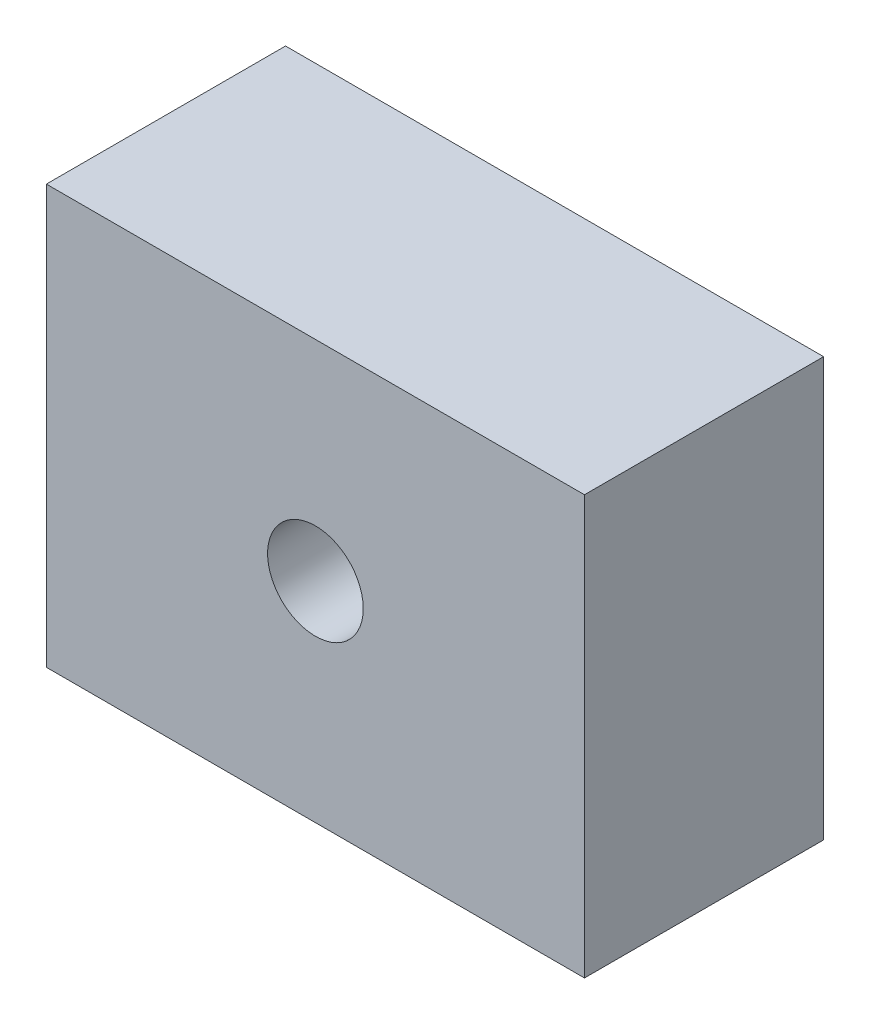
SolidWorks part; units mm, degrees
ref_plane "Front" through (0, 0, 0) normal (0, 0, 1) x (1, 0, 0)
ref_plane "Top" through (0, 0, 0) normal (0, 1, 0) x (1, 0, 0)
ref_plane "Right" through (0, 0, 0) normal (1, 0, 0) x (0, 0, -1)
sketch "Sketch1" plane through (0, 0, 0) normal (0, 0, 1) x (1, 0, 0)
  line L1 (0, 0) -> (45, 0)
  line L2 (0, 0) -> (0, 35)
  line L3 (0, 35) -> (45, 35)
  line L4 (45, 0) -> (45, 35)
  dimension "D1" = 35
  dimension "D2" = 45
extrude "Boss-Extrude1" add sketch "Sketch1" along normal blind 20
sketch "Sketch2" plane through (0, 0, 20) normal (0, 0, 1) x (1, 0, 0)
  line L0 (0, 35) -> (0, 0) construction
  line L2 (45, 35) -> (0, 35) construction
  circle A0 centre (22.5, 17.5) radius 4
  dimension "D1" = 8
  dimension "D2" = 22.5
  dimension "D3" = 17.5
extrude "Cut-Extrude1" cut sketch "Sketch2" against normal through all
